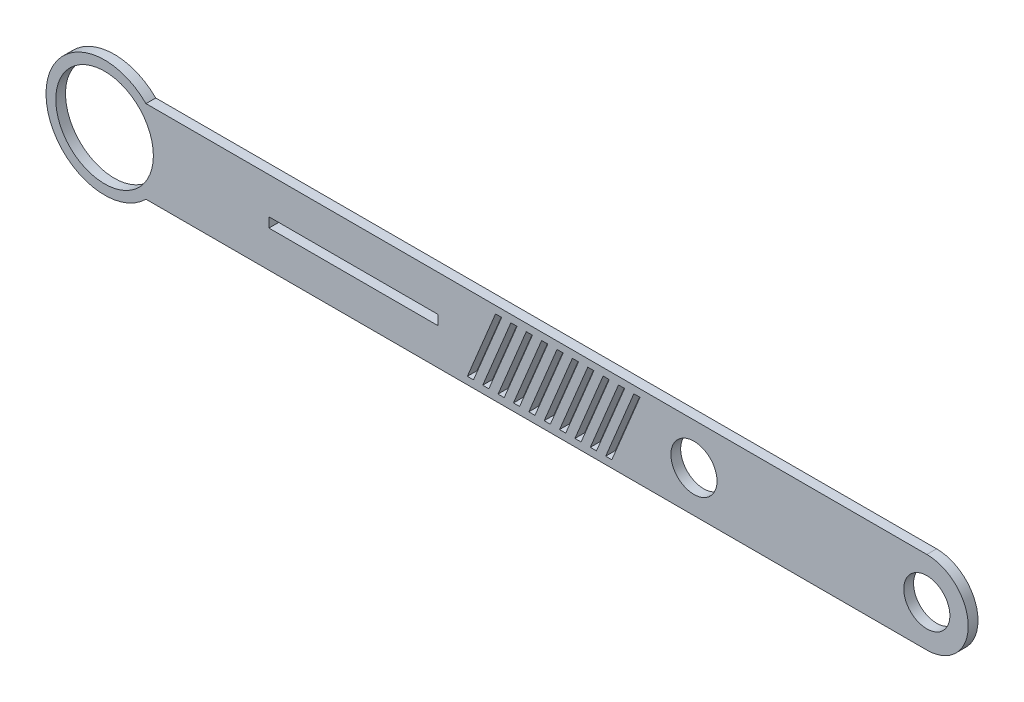
SolidWorks part; units mm, degrees
ref_plane "Front Plane" through (0, 0, 0) normal (0, 0, 1) x (1, 0, 0)
ref_plane "Top Plane" through (0, 0, 0) normal (0, 1, 0) x (1, 0, 0)
ref_plane "Right Plane" through (0, 0, 0) normal (1, 0, 0) x (0, 0, -1)
sketch "Sketch1" plane through (0, 0, 0) normal (0, 0, 1) x (1, 0, 0)
  line L3 (13.4704, 13.4704) -> (267.4704, 13.4704)
  line L4 (13.4704, -13.4704) -> (267.4704, -13.4704)
  line L6 (13.4704, 13.4704) -> (53.4704, 13.4704)
  line L8 (122.5889, 0) -> (118.0016, -11.0886)
  line L9 (108.4704, 1.5875) -> (108.4704, -1.5875)
  line L10 (108.4704, 1.5875) -> (53.4704, 1.5875)
  line L11 (108.4704, -1.5875) -> (53.4704, -1.5875)
  line L12 (53.4704, -1.5875) -> (53.4704, 1.5875)
  line L13 (122.5889, 0) -> (127.1762, 11.0886)
  line L14 (127.1762, 11.0886) -> (129.1762, 11.0886)
  line L15 (129.1762, 11.0886) -> (120.0016, -11.0886)
  line L16 (120.0016, -11.0886) -> (118.0016, -11.0886)
  line L22 (134.1762, 11.0886) -> (125.0016, -11.0886)
  line L23 (127.5889, 0) -> (132.1762, 11.0886)
  line L24 (127.5889, 0) -> (123.0016, -11.0886)
  line L25 (132.1762, 11.0886) -> (134.1762, 11.0886)
  line L26 (125.0016, -11.0886) -> (123.0016, -11.0886)
  line L27 (139.1762, 11.0886) -> (130.0016, -11.0886)
  line L28 (132.5889, 0) -> (137.1762, 11.0886)
  line L29 (132.5889, 0) -> (128.0016, -11.0886)
  line L30 (137.1762, 11.0886) -> (139.1762, 11.0886)
  line L31 (130.0016, -11.0886) -> (128.0016, -11.0886)
  line L32 (144.1762, 11.0886) -> (135.0016, -11.0886)
  line L33 (137.5889, 0) -> (142.1762, 11.0886)
  line L34 (137.5889, 0) -> (133.0016, -11.0886)
  line L35 (142.1762, 11.0886) -> (144.1762, 11.0886)
  line L36 (135.0016, -11.0886) -> (133.0016, -11.0886)
  line L37 (149.1762, 11.0886) -> (140.0016, -11.0886)
  line L38 (142.5889, 0) -> (147.1762, 11.0886)
  line L39 (142.5889, 0) -> (138.0016, -11.0886)
  line L40 (147.1762, 11.0886) -> (149.1762, 11.0886)
  line L41 (140.0016, -11.0886) -> (138.0016, -11.0886)
  line L42 (154.1762, 11.0886) -> (145.0016, -11.0886)
  line L43 (147.5889, 0) -> (152.1762, 11.0886)
  line L44 (147.5889, 0) -> (143.0016, -11.0886)
  line L45 (152.1762, 11.0886) -> (154.1762, 11.0886)
  line L46 (145.0016, -11.0886) -> (143.0016, -11.0886)
  line L47 (159.1762, 11.0886) -> (150.0016, -11.0886)
  line L48 (152.5889, 0) -> (157.1762, 11.0886)
  line L49 (152.5889, 0) -> (148.0016, -11.0886)
  line L50 (157.1762, 11.0886) -> (159.1762, 11.0886)
  line L51 (150.0016, -11.0886) -> (148.0016, -11.0886)
  line L52 (164.1762, 11.0886) -> (155.0016, -11.0886)
  line L53 (157.5889, 0) -> (162.1762, 11.0886)
  line L54 (157.5889, 0) -> (153.0016, -11.0886)
  line L55 (162.1762, 11.0886) -> (164.1762, 11.0886)
  line L56 (155.0016, -11.0886) -> (153.0016, -11.0886)
  line L57 (169.1762, 11.0886) -> (160.0016, -11.0886)
  line L58 (162.5889, 0) -> (167.1762, 11.0886)
  line L59 (162.5889, 0) -> (158.0016, -11.0886)
  line L60 (167.1762, 11.0886) -> (169.1762, 11.0886)
  line L61 (160.0016, -11.0886) -> (158.0016, -11.0886)
  line L62 (174.1762, 11.0886) -> (165.0016, -11.0886)
  line L63 (167.5889, 0) -> (172.1762, 11.0886)
  line L64 (167.5889, 0) -> (163.0016, -11.0886)
  line L65 (172.1762, 11.0886) -> (174.1762, 11.0886)
  line L66 (165.0016, -11.0886) -> (163.0016, -11.0886)
  arc A0 (13.4704, 13.4704) -> (13.4704, -13.4704) centre (0, 0) ccw
  circle A1 centre (0, 0) radius 15.875
  arc A2 (267.4704, 13.4704) -> (267.4704, -13.4704) centre (267.4704, 0) cw
  circle A3 centre (267.4704, 0) radius 7.5
  circle A4 centre (191.7204, 0) radius 7.5
  point P18 (108.4704, 0)
  dimension "D1" = 38.1
  dimension "D2" = 31.75
  dimension "D6" = 15
  dimension "D5" = 254
  dimension "D7" = 40
  dimension "D11" = 10
extrude "Boss-Extrude1" add sketch "Sketch1" along normal blind 3.175 contours A2 L3 A0 L4 A4 A3 A1 L11 L12 L10 L9 L15 L16 L8 L13 L14 L22 L26 L24 L23 L25 L27 L31 L29 L28 L30 L32 L36 L34 L33 L35 L37 L41 L39 L38 L40 L42 L46 L44 L43
